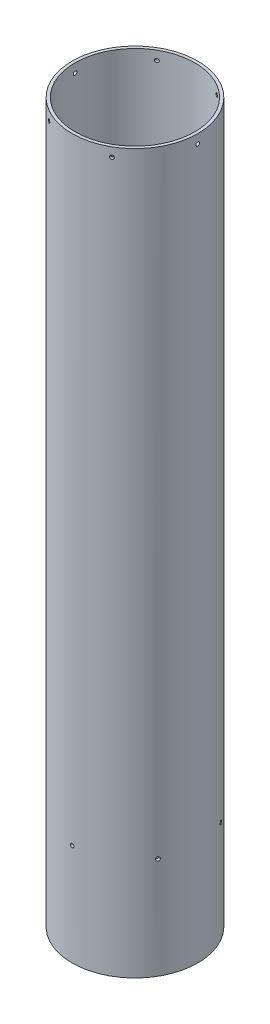
SolidWorks part; units mm, degrees
ref_plane "Front Plane" through (0, 0, 0) normal (0, 0, 1) x (1, 0, 0)
ref_plane "Top Plane" through (0, 0, 0) normal (0, 1, 0) x (1, 0, 0)
ref_plane "Right Plane" through (0, 0, 0) normal (1, 0, 0) x (0, 0, -1)
sketch "Sketch1" plane through (0, 0, 0) normal (0, 1, 0) x (1, 0, 0)
  line L0 (0, 0) -> (-6412.266, 0) construction
  line L1 (0, 0) -> (0, 8725.9702) construction
  circle A0 centre (0, 0) radius 105
  circle A1 centre (0, 0) radius 100
  dimension "D1" = 210
  dimension "D2" = 200
extrude "Boss-Extrude1" add sketch "Sketch1" along normal blind 1200
sketch "Sketch2" plane through (0, 0, 0) normal (1, 0, 0) x (0, 0, -1)
  line L0 (0, 800) -> (0, 720.2322) construction
  line L2 (100, 1200) -> (-100, 1200) construction
  circle A1 centre (0, 1185) radius 3.05
  dimension "D1" = 6.1
  dimension "D2" = 15
extrude "Cut-Extrude1" cut sketch "Sketch2" against normal up to next contours A1
pattern_circular "CirPattern1" count 6 over 360 about axis through (0, 1200, 0) along (0, 1, 0) of "Cut-Extrude1"
sketch "Sketch3" plane through (0, 0, 0) normal (0, 0, 1) x (1, 0, 0)
  line L0 (0, 1200) -> (0, 0) construction
  line L3 (100, 1200) -> (-100, 1200) construction
  circle A0 centre (0, 170) radius 3.05
  dimension "D2" = 6.1
  dimension "D1" = 1030
extrude "Cut-Extrude2" cut sketch "Sketch3" against normal through all
pattern_circular "CirPattern2" count 6 over 360 about axis through (0, 0, 0) along (0, 1, 0) of "Cut-Extrude2"
equation "\"th\"= 10"
equation "\"D2@Sketch1\"=\"D1@Sketch1\"-\"th\""
